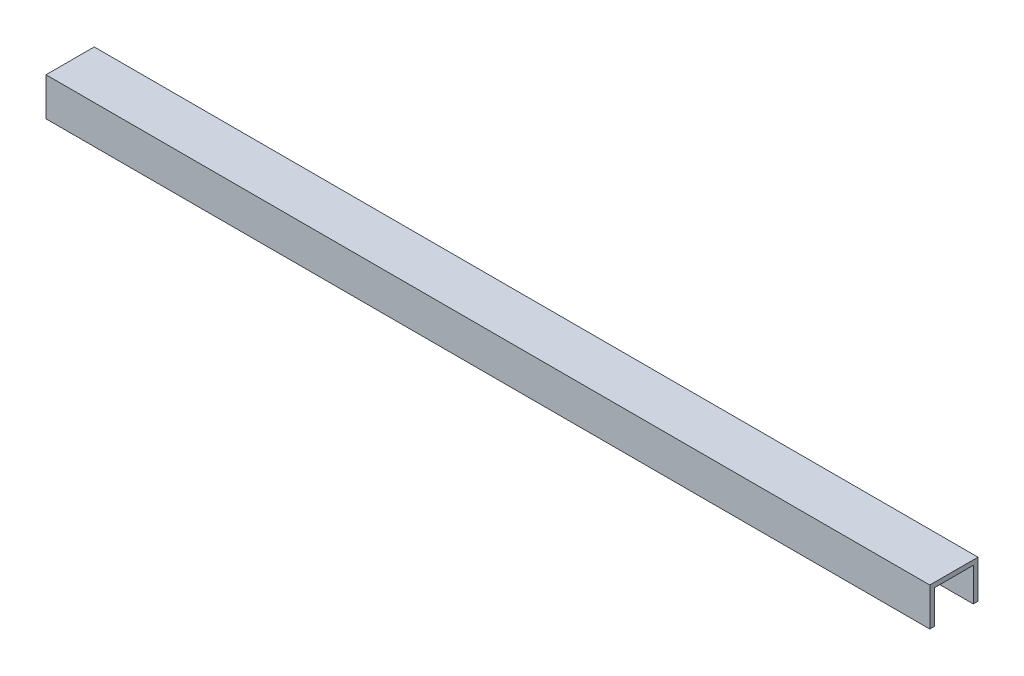
SolidWorks part; units mm, degrees
ref_plane "Front Plane" through (0, 0, 0) normal (0, 0, 1) x (1, 0, 0)
ref_plane "Top Plane" through (0, 0, 0) normal (0, 1, 0) x (1, 0, 0)
ref_plane "Right Plane" through (0, 0, 0) normal (1, 0, 0) x (0, 0, -1)
sketch "end channel sketch" plane through (0, 0, 0) normal (1, 0, 0) x (0, 0, -1)
  line L0 (-13.83, 294.27) -> (-13.83, 306.97)
  line L1 (-13.83, 306.97) -> (-29.87, 306.97)
  line L2 (-29.87, 306.97) -> (-29.87, 294.27)
  line L3 (-29.87, 294.27) -> (-28.3, 294.27)
  line L4 (-28.3, 294.27) -> (-28.3, 305.4)
  line L5 (-28.3, 305.4) -> (-15.4, 305.4)
  line L6 (-15.4, 305.4) -> (-15.4, 294.27)
  line L7 (-15.4, 294.27) -> (-13.83, 294.27)
extrude "end channel" add sketch "end channel sketch" along normal mid plane 294.04
equation "\"diffL\" = 608.8mm"
equation "\"diffW\" = 329.4mm"
equation "\"diffT\" = 2.9mm"
equation "\"chanSlotW\" = 12.9mm"
equation "\"chanSlotDepth\" = 11.13mm"
equation "\"chanFloor\" = 1.57mm"
equation "\"chanLeg\" = 12.7mm"
equation "\"lightL\" = 604.8mm"
equation "\"lightW\" = 330.2mm"
equation "\"lightH\" = 92mm"
equation "\"lightSideFlat\" = 30mm"
equation "\"lightSlopeLen\" = 38.9mm"
equation "\"lightWingDepth\" = 50.1mm"
equation "\"lightWingFlat\" = 90.2mm"
equation "\"lightChanW\" = 99.6mm"
equation "\"lightChanStand\" = 44.1mm"
equation "\"insFlangeD\" = 12.3mm"
equation "\"insFromEnd\" = 20.7mm"
equation "\"insUpSlope\" = 20.8mm"
equation "\"gaugeH\" = 10mm"
equation "\"gaugeStepLen\" = 14mm"
equation "\"gaugeStepW0\" = 13.1mm"
equation "\"gaugeStepDW\" = 0.2mm"
equation "\"gaugeSteps\" = 5mm"
equation "\"gaugeHandleLen\" = 30mm"
equation "\"gaugeHandleW\" = 24mm"
equation "\"gaugeSlot0\" = 3mm"
equation "\"gaugeSlotD\" = 0.1mm"
equation "\"gaugeSlotDepth\" = 8mm"
equation "\"gap\" = 25.4mm"
equation "\"edgeL\" = 1mm"
equation "\"edgeW\" = 0.75mm"
equation "\"proud\" = 2.5mm"
equation "\"seatClr\" = 0.15mm"
equation "\"tongueClrZ\" = 0.1mm"
equation "\"tongueClrX\" = 0.25mm"
equation "\"tongueLen\" = 30mm"
equation "\"armSide\" = 45mm"
equation "\"armEnd\" = 20mm"
equation "\"brkW\" = 26mm"
equation "\"brkT\" = 7mm"
equation "\"brkSeatClr\" = 0.3mm"
equation "\"brkScrewSpan\" = 16mm"
equation "\"pilotD\" = 2.7mm"
equation "\"pilotDepth\" = 10mm"
equation "\"screwClrD\" = 3.9mm"
equation "\"jogBelow\" = 4mm"
equation "\"padT\" = 7mm"
equation "\"padLen\" = 36mm"
equation "\"m6Clr\" = 9mm"
equation "\"m6Slot\" = 5mm"
equation "\"flangeRelD\" = 18mm"
equation "\"flangeRelDepth\" = 1.5mm"
equation "\"relLen\" = 5mm"
equation "\"relDepth\" = 3.3mm"
equation "\"knockN\" = 100mm"
equation "\"petgcfE\" = 3000mm"
equation "\"mockExtent\" = 110mm"
equation "\"relZnear\" = 9.4mm"
equation "\"relZfar\" = 23.4mm"
equation "\"headD\" = 8mm"
equation "\"headH\" = 2.5mm"
equation "\"headFromEnd\" = 6.8mm"
equation "\"headBack\" = 16.4mm"
equation "\"sideClr\" = 0.4mm"
equation "\"cornerRelR\" = 1.5mm"
equation "\"cornerRelBack\" = 0.6mm"
equation "\"endHeadH\" = 2.8mm"
equation "\"footClr\" = 1.2mm"
equation "\"footEndClr\" = 3.5mm"
equation "\"footLift\" = 6mm"
equation "\"footBlockClr\" = 0.5mm"
equation "\"footBack\" = 50mm"
equation "\"footFwd\" = 10mm"
equation "\"footBraceEnd\" = 3mm"
equation "\"footLoadN\" = 25mm"
equation "\"spacerLen\" = 60mm"
equation "\"spacerShort\" = 0.5mm"
equation "\"spacerCham\" = 0.8mm"
equation "\"spacerPerSide\" = 3mm"
equation "\"spacerPerEnd\" = 1mm"
equation "\"toolR\" = 9mm"
equation "\"visR\" = 4mm"
equation "\"edgeR\" = 1mm"
equation "\"bendOutR\" = 5mm"
equation "\"insideR\" = 2.5mm"
equation "\"footCornerR\" = 10mm"
equation "\"footFrontR\" = 8mm"
equation "\"braceKinkR\" = 12mm"
equation "\"bedCham\" = 1mm"
equation "\"bedChamSmall\" = 0.6mm"
equation "\"soleTopR\" = 2mm"
equation "\"cornerR\" = 6mm"
equation "\"rimInR\" = 1mm"
equation "\"insFlangeH\" = 1mm"
